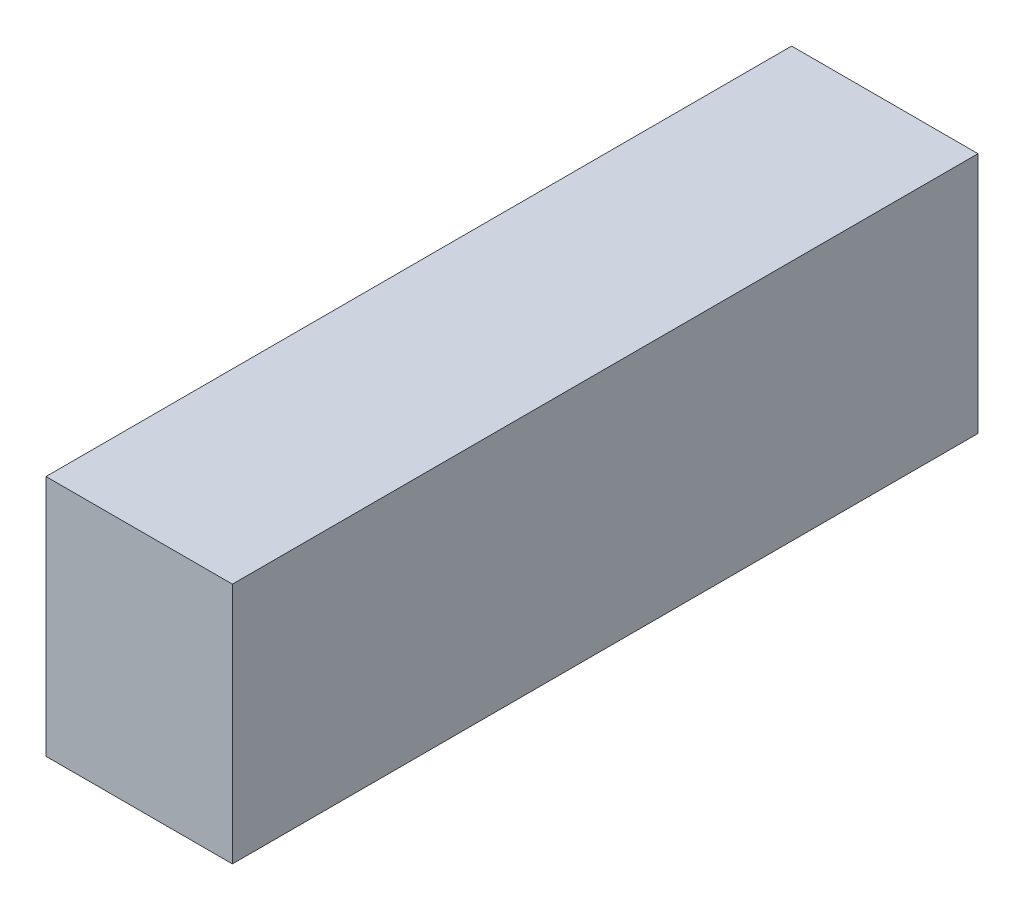
SolidWorks part; units mm, degrees
ref_plane "Front Plane" through (0, 0, 0) normal (0, 0, 1) x (1, 0, 0)
ref_plane "Top Plane" through (0, 0, 0) normal (0, 1, 0) x (1, 0, 0)
ref_plane "Right Plane" through (0, 0, 0) normal (1, 0, 0) x (0, 0, -1)
sketch "Sketch1" plane through (0, 0, 0) normal (1, 0, 0) x (0, 0, -1)
  line L1 (0, 0) -> (40, 0)
  line L2 (0, 0) -> (0, 13)
  line L3 (0, 13) -> (40, 13)
  line L4 (40, 0) -> (40, 13)
extrude "Boss-Extrude1" add sketch "Sketch1" against normal blind 10
